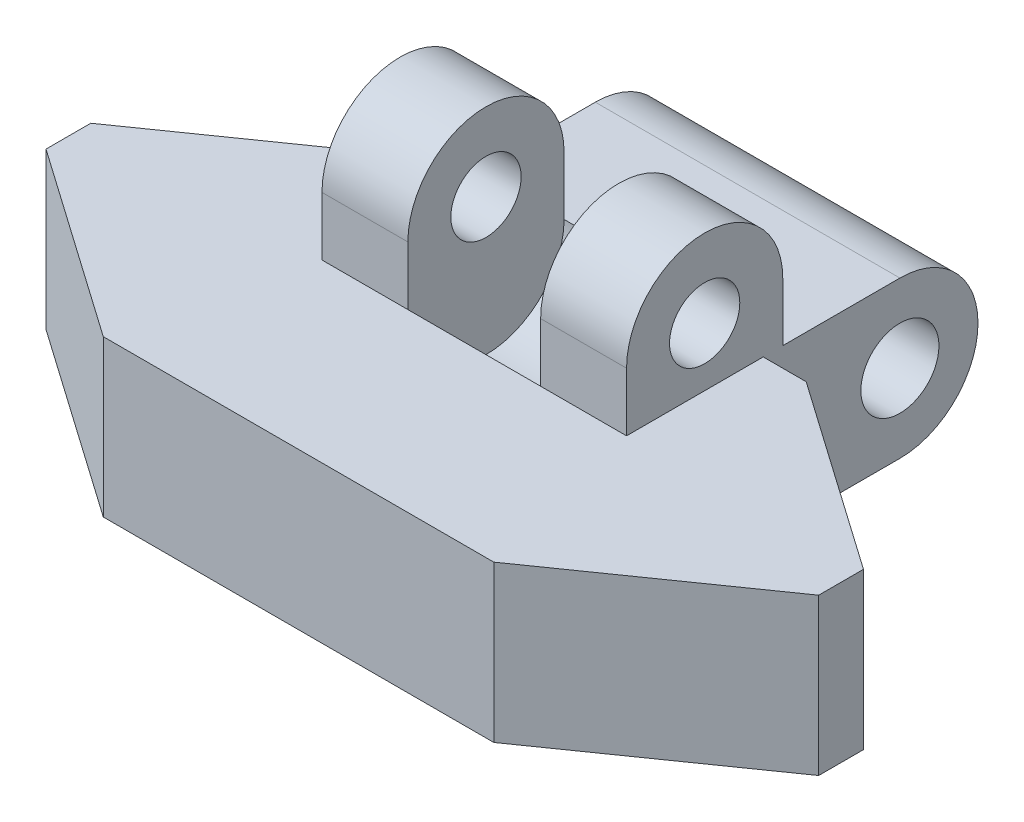
SolidWorks part; units mm, degrees
ref_plane "Front Plane" through (0, 0, 0) normal (0, 0, 1) x (1, 0, 0)
ref_plane "Top Plane" through (0, 0, 0) normal (0, 1, 0) x (1, 0, 0)
ref_plane "Right Plane" through (0, 0, 0) normal (1, 0, 0) x (0, 0, -1)
sketch "Sketch1" plane through (0, 0, 0) normal (0, 1, 0) x (1, 0, 0)
  line L1 (-5, 4) -> (5, 4)
  line L3 (-5, -4) -> (5, -4)
  line L5 (0, -4) -> (0, 4) construction
  line L6 (-5, 0) -> (5, 0) construction
  line L12 (9.8934, -0.5736) -> (5, -4)
  line L13 (9.8934, 0.5736) -> (5, 4)
  line L14 (-9.8934, 0.5736) -> (-5, 4)
  line L15 (-9.8934, -0.5736) -> (-5, -4)
  line L17 (-9.8934, -0.5736) -> (-9.8934, 0.5736)
  line L18 (9.8934, 0.5736) -> (9.8934, -0.5736)
  point P3 (-10.7126, 0)
  point P4 (10.7126, 0)
  point P14 (0, 0)
  point P180 (0, 0)
  dimension "D1" = 8
  dimension "D2" = 10
  dimension "D6" = 215
  dimension "D7" = 35
extrude "Boss-Extrude1" add sketch "Sketch1" along normal blind 4
sketch "Sketch2" plane through (0, 0, 0) normal (1, 0, 0) x (0, 0, -1)
  line L1 (4, 4) -> (7.5, 4)
  line L2 (4, 4) -> (4, 0)
  line L3 (4, 0) -> (7.5, 0)
  line L5 (5.75, 0) -> (5.75, 4) construction
  line L6 (4, 2) -> (7.5, 2) construction
  line L7 (0.5736, 0) -> (4, 0) construction
  arc A1 (7.5, 0) -> (7.5, 4) centre (7.5, 2) ccw
  circle A2 centre (7.5, 2) radius 1
  point P312 (5.75, 2)
  dimension "D2" = 2
  dimension "D1" = 3.5
extrude "Boss-Extrude2" add sketch "Sketch2" along normal blind 3.9 and the other way blind 3.9
sketch "Sketch4" plane through (0, 0, 0) normal (1, 0, 0) x (0, 0, -1)
  line L1 (0.5, 4) -> (4.5, 4)
  line L2 (0.5, 4) -> (0.5, 5.5)
  line L4 (4.5, 4) -> (4.5, 5.5)
  line L5 (2.5, 5.5) -> (2.5, 4) construction
  line L6 (0.5, 4.75) -> (4.5, 4.75) construction
  line L7 (-4, 4) -> (-0.5736, 4) construction
  arc A0 (4.5, 5.5) -> (0.5, 5.5) centre (2.5, 5.5) ccw
  circle A1 centre (2.5, 5.5) radius 0.9
  circle A2 centre (7.5, 2) radius 1 construction
  point P148 (2.5, 4.75)
  dimension "D3" = 1.8
  dimension "D1" = 4
  dimension "D2" = 1.5
  dimension "D4" = 5
extrude "Boss-Extrude3" add sketch "Sketch4" along normal blind 3.9 and the other way blind 3.9
sketch "Sketch5" plane through (0, 0, 4) normal (0, 0, 1) x (1, 0, 0)
  line L0 (3.9, 7.5) -> (-3.9, 7.5) construction
  line L1 (-1.7, 7.5) -> (1.7, 7.5)
  line L2 (-1.7, 7.5) -> (-1.7, 4)
  line L3 (-1.7, 4) -> (1.7, 4)
  line L4 (1.7, 7.5) -> (1.7, 4)
  line L5 (0, 4) -> (0, 7.5) construction
  line L6 (-1.7, 5.75) -> (1.7, 5.75) construction
  line L7 (-3.9, 5.5) -> (-3.9, 4) construction
  line L8 (3.9, 5.5) -> (3.9, 4) construction
  line L9 (-5, 4) -> (5, 4) construction
  point P428 (0, 5.75)
  dimension "D1" = 3.4
extrude "Cut-Extrude1" cut sketch "Sketch5" against normal up to next
sketch "Sketch6" plane through (1.7, 0, 0) normal (-1, 0, 0) x (0, 0, 1)
  line L2 (-4.5, 4) -> (-0.5, 4) construction
  line L3 (-4.5, 4) -> (-0.5, 4)
  arc A1 (-4.5, 4) -> (-0.5, 4) centre (-2.5, 4) ccw
  dimension "D1" = 4
extrude "Cut-Extrude2" cut sketch "Sketch6" along normal up to surface (3.4 mm away) up to face at (-1.7, 5.5, -1.6)
